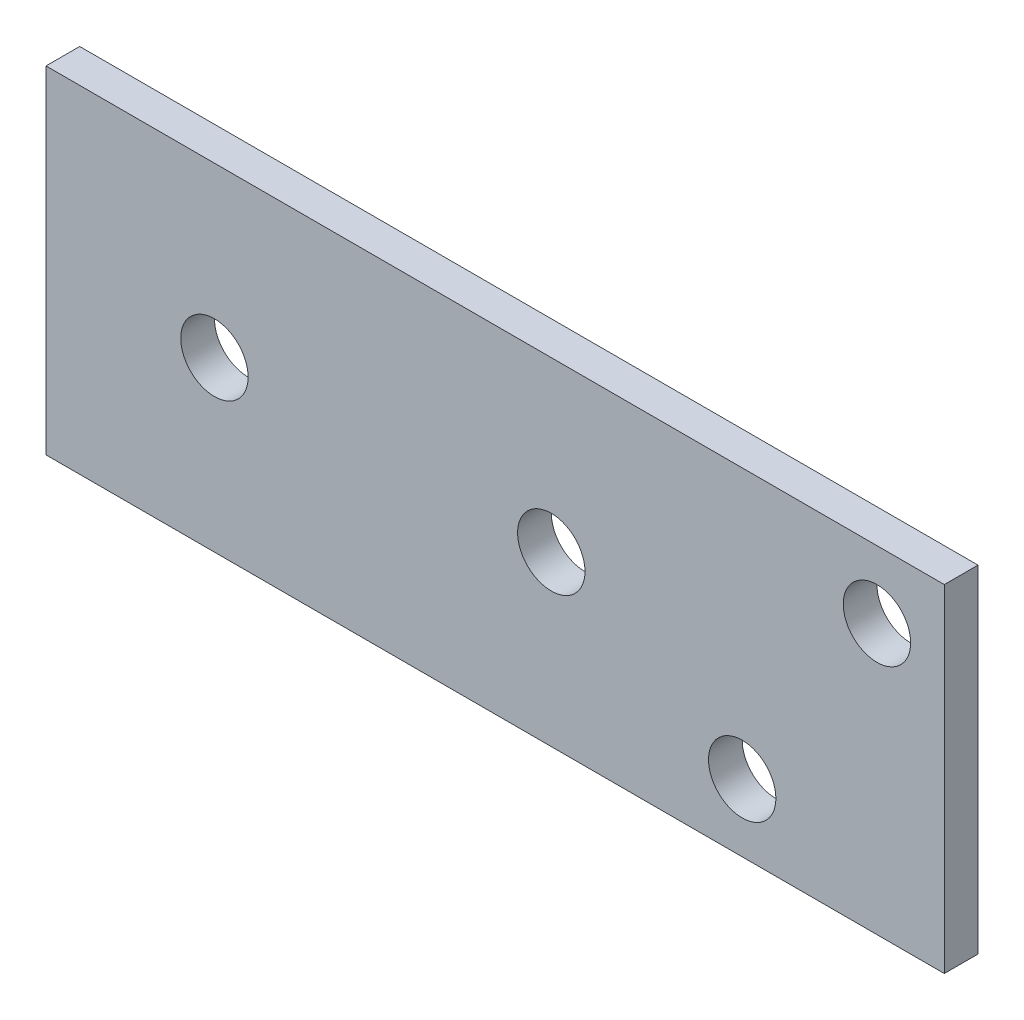
SolidWorks part; units mm, degrees
ref_plane "Plan de face" through (0, 0, 0) normal (0, 0, 1) x (1, 0, 0)
ref_plane "Plan de dessus" through (0, 0, 0) normal (0, 1, 0) x (1, 0, 0)
ref_plane "Plan de droite" through (0, 0, 0) normal (1, 0, 0) x (0, 0, -1)
sketch "Esquisse1" plane through (0, 0, 0) normal (0, 0, 1) x (1, 0, 0)
  line L1 (-27.9102, 11.4437) -> (12.0898, 11.4437)
  line L2 (-27.9102, 11.4437) -> (-27.9102, -3.5563)
  line L3 (-27.9102, -3.5563) -> (12.0898, -3.5563)
  line L4 (12.0898, 11.4437) -> (12.0898, -3.5563)
  circle A0 centre (-20.4102, 3.9437) radius 1.5
  circle A1 centre (-5.4102, 3.9437) radius 1.5
  dimension "D3" = 7.5
  dimension "D5" = 15
  dimension "D1" = 15
  dimension "D2" = 40
  dimension "D4" = 7.5
extrude "Extrusion1" add sketch "Esquisse1" along normal blind 1.5
sketch "Esquisse2" plane through (0, 0, 1.5) normal (0, 0, 1) x (1, 0, 0)
  line L0 (-27.9102, -3.5563) -> (12.0898, -3.5563) construction
  line L1 (12.0898, 11.4437) -> (-27.9102, 11.4437) construction
  line L2 (12.0898, -3.5563) -> (12.0898, 11.4437) construction
  circle A0 centre (9.0898, 8.4437) radius 1.5
  circle A1 centre (3.0898, -0.5563) radius 1.5
  dimension "D1" = 3
  dimension "D2" = 3
  dimension "D3" = 3
  dimension "D4" = 9
extrude "Extrusion2" cut sketch "Esquisse2" against normal blind 1.5
